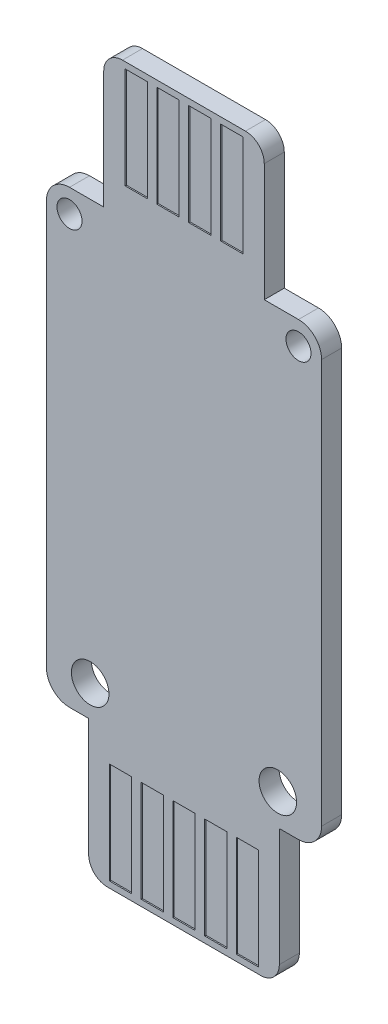
SolidWorks part; units mm, degrees
ref_plane "前视基准面" through (0, 0, 0) normal (0, 0, 1) x (1, 0, 0)
ref_plane "上视基准面" through (0, 0, 0) normal (0, 1, 0) x (1, 0, 0)
ref_plane "右视基准面" through (0, 0, 0) normal (1, 0, 0) x (0, 0, -1)
other "Configuration Table"
sketch "草图1" plane through (0, 0, 0) normal (0, 0, 1) x (1, 0, 0)
  line L1 (-9.15, 16) -> (9.15, 16)
  line L2 (-11, 14.15) -> (-11, -20)
  line L3 (-11, -20) -> (11, -20)
  line L4 (11, 14.15) -> (11, -20)
  arc A0 (-9.15, 16) -> (-11, 14.15) centre (-9.15, 14.15) ccw
  circle A1 centre (-9.15, 14.15) radius 1
  arc A2 (11, 14.15) -> (9.15, 16) centre (9.15, 14.15) ccw
  circle A3 centre (9.15, 14.15) radius 1
  point P0 (0, 0)
  point P6 (0, 0)
  dimension "D5" = 3.7
  dimension "D6" = 2
  dimension "D3" = 3.7
  dimension "D4" = 2
  dimension "D1" = 20
  dimension "D2" = 22
  dimension "D7" = 11
  dimension "D8" = 36
extrude "凸台-拉伸1" add sketch "草图1" along normal blind 1.6
sketch "草图3" plane through (0, 0, 0) normal (0, 0, 1) x (1, 0, 0)
  line L0 (-11, -20) -> (11, -20) construction
  line L1 (-10, -20) -> (10, -20) construction
  line L2 (-10, -20) -> (-10, 12) construction
  line L3 (-10, 12) -> (10, 12) construction
  line L4 (10, -20) -> (10, 12) construction
  line L5 (-11, 14.15) -> (-11, -20) construction
  circle A0 centre (-7.5, -17.5) radius 1.5
  circle A1 centre (7.5, -17.5) radius 1.5
  dimension "D4" = 3
  dimension "D7" = 3
  dimension "D1" = 32
  dimension "D2" = 20
  dimension "D3" = 1
  dimension "D5" = 2.5
  dimension "D6" = 2.5
  dimension "D8" = 2.5
  dimension "D9" = 2.5
extrude "切除-拉伸1" cut sketch "草图3" along normal blind 1.6
sketch "草图5" plane through (0, 0, 0) normal (0, 0, 1) x (1, 0, 0)
  line L0 (11, -20) -> (11, 14.15) construction
  line L1 (-11, -20) -> (11, -20) construction
  line L2 (-11, 14.15) -> (-11, -20) construction
  line L3 (11, -20) -> (11, -18.15)
  line L4 (-11, -20) -> (-9.15, -20)
  line L5 (-11, -18.15) -> (-11, -20)
  line L6 (9.15, -20) -> (11, -20)
  arc A0 (-11, -18.15) -> (-9.15, -20) centre (-9.15, -18.15) ccw
  arc A1 (9.15, -20) -> (11, -18.15) centre (9.15, -18.15) ccw
  dimension "D1" = 3.7
  dimension "D2" = 3.7
extrude "切除-拉伸2" cut sketch "草图5" along normal up to surface (1.6 mm away) up to face at (-6, -17.5, 1.6)
sketch "草图7" plane through (0, 0, 0) normal (0, 0, 1) x (1, 0, 0)
  line L0 (9.15, 16) -> (-9.15, 16) construction
  line L1 (-4.915, 26.92) -> (4.915, 26.92)
  line L2 (-6.415, 25.42) -> (-6.415, 16)
  line L3 (-6.415, 16) -> (6.415, 16)
  line L4 (6.415, 25.42) -> (6.415, 16)
  line L5 (-9.15, -20) -> (9.15, -20) construction
  line L6 (-6.415, -20) -> (6.415, -20)
  line L7 (-6.415, -20) -> (-6.415, -29.42)
  line L8 (-4.915, -30.92) -> (4.915, -30.92)
  line L9 (6.415, -20) -> (6.415, -29.42)
  arc A0 (-4.915, 26.92) -> (-6.415, 25.42) centre (-4.915, 25.42) ccw
  arc A1 (6.415, 25.42) -> (4.915, 26.92) centre (4.915, 25.42) ccw
  arc A2 (-6.415, -29.42) -> (-4.915, -30.92) centre (-4.915, -29.42) ccw
  arc A3 (4.915, -30.92) -> (6.415, -29.42) centre (4.915, -29.42) ccw
  point P6 (0, 16)
  point P7 (0, 16)
  point P19 (0, -20)
  point P20 (0, -20)
  dimension "D3" = 3
  dimension "D4" = 3
  dimension "D7" = 3
  dimension "D8" = 3
  dimension "D1" = 12.83
  dimension "D2" = 10.92
  dimension "D5" = 10.92
  dimension "D6" = 12.83
extrude "凸台-拉伸2" add sketch "草图7" along normal up to surface (1.6 mm away) up to face at (-6, -17.5, 1.6)
sketch "草图8" plane through (0, 0, 0) normal (0, 0, 1) x (1, 0, 0)
  line L0 (4.915, 26.92) -> (-4.915, 26.92) construction
  line L1 (-2.16, 26.42) -> (-0.38, 26.42)
  line L2 (-2.16, 26.42) -> (-2.16, 18.32)
  line L3 (-2.16, 18.32) -> (-0.38, 18.32)
  line L4 (-0.38, 26.42) -> (-0.38, 18.32)
  line L5 (0, -1000) -> (0, 49000) construction
  line L6 (0, -30.92) -> (0, 26.92) construction
  line L7 (-4.915, -30.92) -> (4.915, -30.92) construction
  line L8 (-1000, -2) -> (49000, -2) construction
  line L9 (-4.7, 26.42) -> (-2.92, 26.42)
  line L10 (-4.7, 26.42) -> (-4.7, 18.32)
  line L11 (-4.7, 18.32) -> (-2.92, 18.32)
  line L12 (-2.92, 26.42) -> (-2.92, 18.32)
  line L13 (-2.16, 26.42) -> (-4.7, 26.42) construction
  line L14 (2.16, 26.42) -> (4.7, 26.42) construction
  line L15 (2.92, 26.42) -> (2.92, 18.32)
  line L16 (4.7, 18.32) -> (2.92, 18.32)
  line L17 (4.7, 26.42) -> (4.7, 18.32)
  line L18 (4.7, 26.42) -> (2.92, 26.42)
  line L19 (0.38, 26.42) -> (0.38, 18.32)
  line L20 (2.16, 18.32) -> (0.38, 18.32)
  line L21 (2.16, 26.42) -> (2.16, 18.32)
  line L22 (2.16, 26.42) -> (0.38, 26.42)
  line L23 (2.16, -30.42) -> (4.7, -30.42) construction
  line L24 (-2.16, -30.42) -> (-4.7, -30.42) construction
  line L25 (0, 996) -> (0, -49004) construction
  line L26 (2.16, -30.42) -> (0.38, -30.42)
  line L27 (2.16, -30.42) -> (2.16, -22.32)
  line L28 (2.16, -22.32) -> (0.38, -22.32)
  line L29 (0.38, -30.42) -> (0.38, -22.32)
  line L30 (4.7, -30.42) -> (2.92, -30.42)
  line L31 (4.7, -30.42) -> (4.7, -22.32)
  line L32 (4.7, -22.32) -> (2.92, -22.32)
  line L33 (2.92, -30.42) -> (2.92, -22.32)
  line L34 (-2.92, -30.42) -> (-2.92, -22.32)
  line L35 (-4.7, -22.32) -> (-2.92, -22.32)
  line L36 (-4.7, -30.42) -> (-4.7, -22.32)
  line L37 (-4.7, -30.42) -> (-2.92, -30.42)
  line L38 (-0.38, -30.42) -> (-0.38, -22.32)
  line L39 (-2.16, -22.32) -> (-0.38, -22.32)
  line L40 (-2.16, -30.42) -> (-2.16, -22.32)
  line L41 (-2.16, -30.42) -> (-0.38, -30.42)
  point P16 (0, -2)
  dimension "D1" = 1.78
  dimension "D2" = 8.1
  dimension "D3" = 0.5
  dimension "D4" = 0.38
  dimension "D5" = 2
  dimension "D6" = 2.54
extrude "切除-拉伸3" cut sketch "草图8" along normal blind 0.1
sketch "草图9" plane through (0, 0, 0) normal (0, 0, 1) x (1, 0, 0)
  line L4 (-0.38, 26.42) -> (-2.16, 26.42)
  line L5 (-0.38, 18.32) -> (-0.38, 26.42)
  line L6 (-2.16, 18.32) -> (-0.38, 18.32)
  line L7 (-2.16, 26.42) -> (-2.16, 18.32)
  line L8 (-0.38, 26.42) -> (-2.16, 26.42)
  line L9 (-0.38, 18.32) -> (-0.38, 26.42)
  line L10 (-2.16, 18.32) -> (-0.38, 18.32)
  line L11 (-2.16, 26.42) -> (-2.16, 18.32)
  line L12 (0.38, 26.42) -> (0.38, 18.32)
  line L13 (0.38, 18.32) -> (2.16, 18.32)
  line L14 (2.16, 18.32) -> (2.16, 26.42)
  line L15 (2.16, 26.42) -> (0.38, 26.42)
  line L16 (0.38, 26.42) -> (0.38, 18.32)
  line L17 (0.38, 18.32) -> (2.16, 18.32)
  line L18 (2.16, 18.32) -> (2.16, 26.42)
  line L19 (2.16, 26.42) -> (0.38, 26.42)
  line L20 (2.92, 26.42) -> (2.92, 18.32)
  line L21 (2.92, 18.32) -> (4.7, 18.32)
  line L22 (4.7, 18.32) -> (4.7, 26.42)
  line L23 (4.7, 26.42) -> (2.92, 26.42)
  line L24 (2.92, 26.42) -> (2.92, 18.32)
  line L25 (2.92, 18.32) -> (4.7, 18.32)
  line L26 (4.7, 18.32) -> (4.7, 26.42)
  line L27 (4.7, 26.42) -> (2.92, 26.42)
  line L28 (-2.92, 26.42) -> (-4.7, 26.42)
  line L29 (-2.92, 18.32) -> (-2.92, 26.42)
  line L30 (-4.7, 18.32) -> (-2.92, 18.32)
  line L31 (-4.7, 26.42) -> (-4.7, 18.32)
  line L32 (-2.92, 26.42) -> (-4.7, 26.42)
  line L33 (-2.92, 18.32) -> (-2.92, 26.42)
  line L34 (-4.7, 18.32) -> (-2.92, 18.32)
  line L35 (-4.7, 26.42) -> (-4.7, 18.32)
  line L36 (-0.38, -30.42) -> (-0.38, -22.32)
  line L37 (-0.38, -22.32) -> (-2.16, -22.32)
  line L38 (-2.16, -22.32) -> (-2.16, -30.42)
  line L39 (-2.16, -30.42) -> (-0.38, -30.42)
  line L40 (-0.38, -30.42) -> (-0.38, -22.32)
  line L41 (-0.38, -22.32) -> (-2.16, -22.32)
  line L42 (-2.16, -22.32) -> (-2.16, -30.42)
  line L43 (-2.16, -30.42) -> (-0.38, -30.42)
  line L44 (-2.92, -30.42) -> (-2.92, -22.32)
  line L45 (-2.92, -22.32) -> (-4.7, -22.32)
  line L46 (-4.7, -22.32) -> (-4.7, -30.42)
  line L47 (-4.7, -30.42) -> (-2.92, -30.42)
  line L48 (-2.92, -30.42) -> (-2.92, -22.32)
  line L49 (-2.92, -22.32) -> (-4.7, -22.32)
  line L50 (-4.7, -22.32) -> (-4.7, -30.42)
  line L51 (-4.7, -30.42) -> (-2.92, -30.42)
  line L52 (2.92, -30.42) -> (4.7, -30.42)
  line L53 (4.7, -30.42) -> (4.7, -22.32)
  line L54 (4.7, -22.32) -> (2.92, -22.32)
  line L55 (2.92, -22.32) -> (2.92, -30.42)
  line L56 (2.92, -30.42) -> (4.7, -30.42)
  line L57 (4.7, -30.42) -> (4.7, -22.32)
  line L58 (4.7, -22.32) -> (2.92, -22.32)
  line L59 (2.92, -22.32) -> (2.92, -30.42)
  line L60 (0.38, -30.42) -> (2.16, -30.42)
  line L61 (2.16, -30.42) -> (2.16, -22.32)
  line L62 (2.16, -22.32) -> (0.38, -22.32)
  line L63 (0.38, -22.32) -> (0.38, -30.42)
  line L64 (0.38, -30.42) -> (2.16, -30.42)
  line L65 (2.16, -30.42) -> (2.16, -22.32)
  line L66 (2.16, -22.32) -> (0.38, -22.32)
  line L67 (0.38, -22.32) -> (0.38, -30.42)
  dimension "D1" = 0
  dimension "D2" = 0
  dimension "D3" = 0
  dimension "D4" = 0
  dimension "D5" = 0
  dimension "D6" = 0
  dimension "D7" = 0
  dimension "D8" = 0
extrude "切除-拉伸4" cut sketch "草图9" against normal blind 0.1 from surface at 1.6 starting at face at (-6, -17.5, 1.6)
sketch "草图11" plane through (0, 0, 0) normal (0, 0, 1) x (1, 0, 0)
  line L0 (6.415, -20) -> (9.15, -20) construction
  line L1 (-7.62, -20) -> (7.62, -20)
  line L2 (-7.62, -20) -> (-7.62, -29.42)
  line L3 (-6.12, -30.92) -> (6.12, -30.92)
  line L4 (7.62, -20) -> (7.62, -29.42)
  line L6 (-4.915, -30.92) -> (4.915, -30.92) construction
  line L7 (4.915, 26.92) -> (-4.915, 26.92) construction
  arc A0 (6.12, -30.92) -> (7.62, -29.42) centre (6.12, -29.42) ccw
  arc A1 (-7.62, -29.42) -> (-6.12, -30.92) centre (-6.12, -29.42) ccw
  point P10 (0, 26.92)
  point P11 (0, -20)
  dimension "D4" = 3
  dimension "D5" = 3
  dimension "D1" = 0
  dimension "D2" = 0
  dimension "D3" = 15.24
extrude "凸台-拉伸3" add sketch "草图11" against normal up to surface (1.6 mm away) from surface at 1.6 up to face at (3.81, 22.37, 0) starting at face at (-6, -17.5, 1.6)
sketch "草图12" plane through (0, 0, 0) normal (0, 0, 1) x (1, 0, 0)
  line L0 (-6.12, -30.92) -> (6.12, -30.92) construction
  line L1 (-0.89, -22.32) -> (0.89, -22.32)
  line L2 (-0.89, -22.32) -> (-0.89, -30.42)
  line L3 (-0.89, -30.42) -> (0.89, -30.42)
  line L4 (0.89, -22.32) -> (0.89, -30.42)
  line L5 (1.65, -22.32) -> (1.65, -30.42)
  line L6 (1.65, -22.32) -> (3.43, -22.32)
  line L7 (3.43, -22.32) -> (3.43, -30.42)
  line L8 (1.65, -30.42) -> (3.43, -30.42)
  line L9 (4.19, -22.32) -> (4.19, -30.42)
  line L10 (4.19, -22.32) -> (5.97, -22.32)
  line L11 (5.97, -22.32) -> (5.97, -30.42)
  line L12 (4.19, -30.42) -> (5.97, -30.42)
  line L13 (-0.89, -22.32) -> (1.65, -22.32) construction
  line L14 (-3.43, -22.32) -> (-3.43, -30.42)
  line L15 (-3.43, -22.32) -> (-1.65, -22.32)
  line L16 (-1.65, -22.32) -> (-1.65, -30.42)
  line L17 (-3.43, -30.42) -> (-1.65, -30.42)
  line L18 (-5.97, -22.32) -> (-5.97, -30.42)
  line L19 (-5.97, -22.32) -> (-4.19, -22.32)
  line L20 (-4.19, -22.32) -> (-4.19, -30.42)
  line L21 (-5.97, -30.42) -> (-4.19, -30.42)
  line L22 (-0.89, -22.32) -> (-3.43, -22.32) construction
  point P6 (0, -22.32)
  dimension "D1" = 1.78
  dimension "D2" = 8.1
  dimension "D3" = 0.5
  dimension "D5" = 2.54
  dimension "D7" = 2.54
  dimension "D4" = 3
  dimension "D6" = 3
extrude "切除-拉伸5" cut sketch "草图12" along normal blind 0.1
sketch "草图13" plane through (0, 0, 0) normal (0, 0, 1) x (1, 0, 0)
  line L4 (1.65, -22.32) -> (1.65, -30.42)
  line L5 (1.65, -30.42) -> (3.43, -30.42)
  line L6 (3.43, -30.42) -> (3.43, -22.32)
  line L7 (3.43, -22.32) -> (1.65, -22.32)
  line L8 (1.65, -22.32) -> (1.65, -30.42)
  line L9 (1.65, -30.42) -> (3.43, -30.42)
  line L10 (3.43, -30.42) -> (3.43, -22.32)
  line L11 (3.43, -22.32) -> (1.65, -22.32)
  line L12 (0.89, -22.32) -> (-0.89, -22.32)
  line L13 (0.89, -30.42) -> (0.89, -22.32)
  line L14 (-0.89, -30.42) -> (0.89, -30.42)
  line L15 (-0.89, -22.32) -> (-0.89, -30.42)
  line L16 (0.89, -22.32) -> (-0.89, -22.32)
  line L17 (0.89, -30.42) -> (0.89, -22.32)
  line L18 (-0.89, -30.42) -> (0.89, -30.42)
  line L19 (-0.89, -22.32) -> (-0.89, -30.42)
  line L20 (-5.97, -22.32) -> (-5.97, -30.42)
  line L21 (-5.97, -30.42) -> (-4.19, -30.42)
  line L22 (-4.19, -30.42) -> (-4.19, -22.32)
  line L23 (-4.19, -22.32) -> (-5.97, -22.32)
  line L24 (-5.97, -22.32) -> (-5.97, -30.42)
  line L25 (-5.97, -30.42) -> (-4.19, -30.42)
  line L26 (-4.19, -30.42) -> (-4.19, -22.32)
  line L27 (-4.19, -22.32) -> (-5.97, -22.32)
  line L28 (-3.43, -22.32) -> (-3.43, -30.42)
  line L29 (-3.43, -30.42) -> (-1.65, -30.42)
  line L30 (-1.65, -30.42) -> (-1.65, -22.32)
  line L31 (-1.65, -22.32) -> (-3.43, -22.32)
  line L32 (-3.43, -22.32) -> (-3.43, -30.42)
  line L33 (-3.43, -30.42) -> (-1.65, -30.42)
  line L34 (-1.65, -30.42) -> (-1.65, -22.32)
  line L35 (-1.65, -22.32) -> (-3.43, -22.32)
  line L36 (4.19, -22.32) -> (4.19, -30.42)
  line L37 (5.97, -22.32) -> (4.19, -22.32)
  line L38 (5.97, -30.42) -> (5.97, -22.32)
  line L39 (4.19, -30.42) -> (5.97, -30.42)
  line L40 (4.19, -22.32) -> (4.19, -30.42)
  line L41 (5.97, -22.32) -> (4.19, -22.32)
  line L42 (5.97, -30.42) -> (5.97, -22.32)
  line L43 (4.19, -30.42) -> (5.97, -30.42)
  dimension "D1" = 0
  dimension "D2" = 0
  dimension "D3" = 0
  dimension "D4" = 0
  dimension "D5" = 0
extrude "切除-拉伸6" cut sketch "草图13" against normal blind 0.1 from surface at 1.6 starting at face at (0, -2, 1.6)
